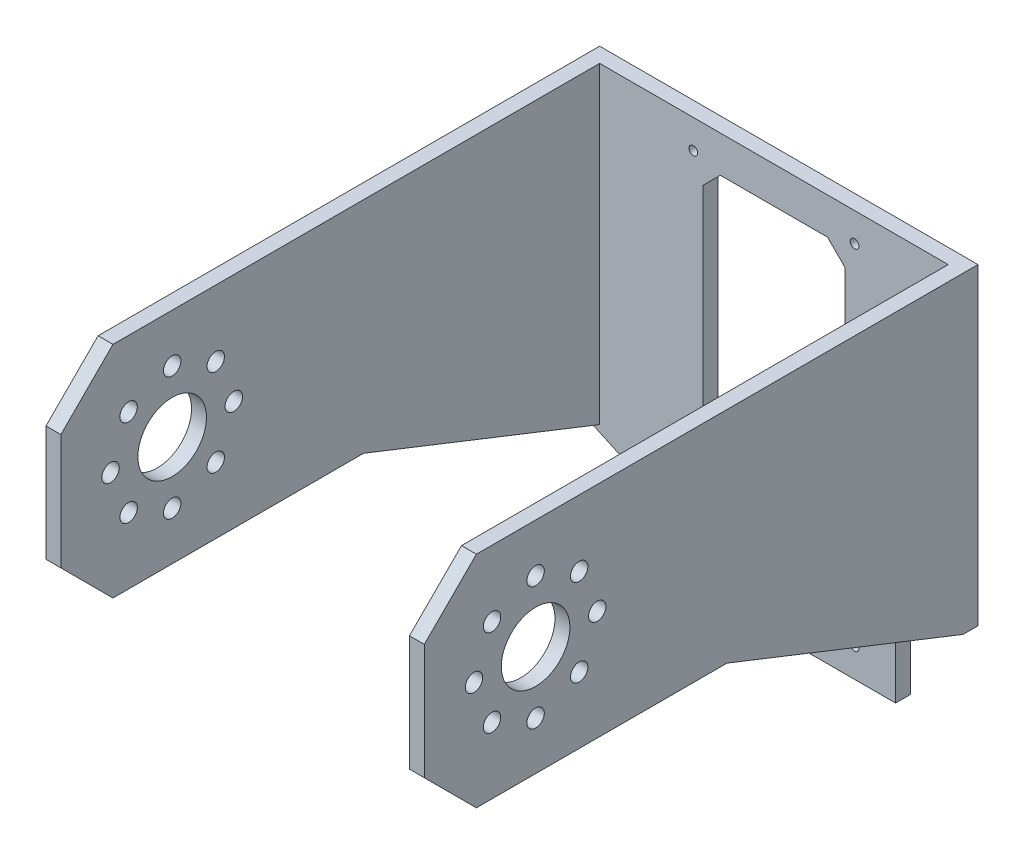
SolidWorks part; units mm, degrees
ref_plane "Front Plane" through (0, 0, 0) normal (0, 0, 1) x (1, 0, 0)
ref_plane "Top Plane" through (0, 0, 0) normal (0, 1, 0) x (1, 0, 0)
ref_plane "Right Plane" through (0, 0, 0) normal (1, 0, 0) x (0, 0, -1)
sketch "Sketch1" plane through (0, 0, -0.0877) normal (0, 1, 0) x (1, 0, 0)
  line L0 (0, 0) -> (-21.71, 0)
  line L1 (-21.71, 0) -> (-21.71, -63.54)
  line L2 (-21.71, -63.54) -> (-20, -63.54)
  line L3 (-20, -63.54) -> (-20, -1.71)
  line L4 (-20, -1.71) -> (0, -1.71)
  line L5 (0, -1.71) -> (0, 0)
  dimension "D1" = 1.71
  dimension "D2" = 1.71
  dimension "D3" = 20
  dimension "D4" = 63.54
extrude "Boss-Extrude1" add sketch "Sketch1" along normal mid plane 25.21
sketch "Sketch2" plane through (-21.71, 0, -0.0877) normal (-1, 0, 0) x (0, 0, 1)
  line L0 (57.565, 12.605) -> (63.54, 6.63)
  line L1 (0, 12.605) -> (63.54, 12.605) construction
  line L2 (63.54, 12.605) -> (63.54, -12.605) construction
  line L3 (63.54, 6.63) -> (63.54, -6.63) construction
  line L4 (63.54, -6.63) -> (57.565, -12.605)
  line L5 (0, -12.605) -> (63.54, -12.605) construction
  line L6 (57.565, -12.605) -> (57.565, 12.605) construction
  line L7 (0.0877, 0) -> (63.54, 0) construction
  line L8 (57.565, 12.605) -> (63.54, 12.605)
  line L9 (63.54, 12.605) -> (63.54, 6.63)
  line L10 (57.565, -12.605) -> (63.54, -12.605)
  line L11 (63.54, -12.605) -> (63.54, -6.63)
  point P11 (63.54, 0)
  dimension "D1" = 13.26
  dimension "D2" = 45
extrude "Cut-Extrude1" cut sketch "Sketch2" against normal blind 32.2
sketch "Sketch3" plane through (-21.71, 0, -0.0877) normal (-1, 0, 0) x (0, 0, 1)
  line L0 (50.77, 12.25) -> (50.77, 0) construction
  line L1 (55.77, -5) -> (45.77, -5) construction
  line L2 (55.77, -5) -> (55.77, 5) construction
  line L3 (55.77, 5) -> (45.77, 5) construction
  line L4 (45.77, -5) -> (45.77, 5) construction
  line L5 (55.77, -5) -> (45.77, 5) construction
  line L6 (55.77, 5) -> (45.77, -5) construction
  line L7 (50.77, 0) -> (63.54, 0) construction
  line L8 (63.54, 6.63) -> (63.54, -6.63) construction
  circle A0 centre (50.77, 0) radius 3.935
  circle A1 centre (45.77, 5) radius 1
  circle A2 centre (55.77, 5) radius 1
  circle A3 centre (55.77, -5) radius 1
  circle A4 centre (45.77, -5) radius 1
  circle A5 centre (50.77, 0) radius 7.0711 construction
  circle A6 centre (43.6989, 0) radius 1
  circle A7 centre (50.77, -7.0711) radius 1
  circle A8 centre (57.8411, 0) radius 1
  circle A9 centre (50.77, 7.0711) radius 1
  dimension "D1" = 7.87
  dimension "D3" = 2
  dimension "D2" = 45
  dimension "D4" = 10
  dimension "D5" = 12.77
extrude "Cut-Extrude2" cut sketch "Sketch3" against normal blind 32.2
mirror "Mirror1" about plane through (0, 12.605, 1.6223) normal (-1, 0, 0) of "Cut-Extrude1", "Boss-Extrude1", "Cut-Extrude2"
sketch "Sketch4" plane through (0, 0, 1.6223) normal (0, 0, 1) x (1, 0, 0)
  line L0 (0, 9.4948) -> (0, 0) construction
  line L1 (5, -5) -> (-5, -5) construction
  line L2 (5, -5) -> (5, 5) construction
  line L3 (5, 5) -> (-5, 5) construction
  line L4 (-5, -5) -> (-5, 5) construction
  line L5 (5, -5) -> (-5, 5) construction
  line L6 (5, 5) -> (-5, -5) construction
  line L7 (7.0711, 0) -> (0, 7.0711) construction
  line L8 (7.0711, 0) -> (0, -7.0711) construction
  line L9 (0, 7.0711) -> (-7.0711, 0) construction
  line L10 (0, -7.0711) -> (-7.0711, 0) construction
  line L11 (7.0711, 0) -> (-7.0711, 0) construction
  line L12 (0, 7.0711) -> (0, -7.0711) construction
  circle A0 centre (0, 0) radius 3.935
  circle A1 centre (-5, 5) radius 1
  circle A2 centre (5, 5) radius 1
  circle A3 centre (5, -5) radius 1
  circle A4 centre (-5, -5) radius 1
  circle A5 centre (-7.0711, 0) radius 1
  circle A6 centre (0, 7.0711) radius 1
  circle A7 centre (7.0711, 0) radius 1
  circle A8 centre (0, -7.0711) radius 1
  dimension "D1" = 7.87
  dimension "D3" = 2
  dimension "D6" = 10
  dimension "D2" = 45
  dimension "D4" = 10
  dimension "D5" = 45
extrude "Cut-Extrude3" [suppressed] cut sketch "Sketch4" against normal blind 32.2
chamfer "Chamfer1" [suppressed] distance 6 angle 45
chamfer "Chamfer2" [suppressed] distance 7 angle 45
sketch "Sketch5" plane through (0, -12.605, -0.0877) normal (0, -1, 0) x (1, 0, 0)
  line L0 (-21.71, 28.8) -> (-20, 28.8)
  line L1 (-21.71, 0) -> (-21.71, 57.565) construction
  line L2 (-20, 57.565) -> (-20, 1.71) construction
  line L3 (-20, 28.8) -> (-20, 1.71)
  line L4 (-20, 1.71) -> (20, 1.71)
  line L5 (20, 1.71) -> (20, 28.8)
  line L6 (20, 57.565) -> (20, 1.71) construction
  line L7 (20, 28.8) -> (21.71, 28.8)
  line L8 (21.71, 0) -> (21.71, 57.565) construction
  line L9 (21.71, 28.8) -> (21.71, 0)
  line L10 (21.71, 0) -> (-21.71, 0)
  line L11 (-21.71, 0) -> (-21.71, 28.8)
  line L12 (-20, 28.8) -> (20, 28.8) construction
  dimension "D1" = 28.8
extrude "Boss-Extrude2" add sketch "Sketch5" along normal blind 21.39
sketch "Sketch6" plane through (0, 0, -0.0877) normal (0, 0, -1) x (-1, 0, 0)
  line L0 (-21.71, 12.605) -> (-21.71, -33.995) construction
  line L1 (-21.71, -26.845) -> (-13.96, -26.845) construction
  line L2 (-21.71, -26.845) -> (-21.71, -33.995)
  line L3 (-21.71, -33.995) -> (-13.96, -33.995)
  line L4 (-13.96, -26.845) -> (-13.96, -33.995)
  line L5 (21.71, -33.995) -> (-21.71, -33.995) construction
  line L6 (-21.71, -26.845) -> (-21.71, -23.295)
  line L7 (-21.71, -23.295) -> (-13.96, -26.845)
  line L8 (0, -33.995) -> (0, 0) construction
  line L9 (21.71, -26.845) -> (13.96, -26.845) construction
  line L10 (21.71, -23.295) -> (13.96, -26.845)
  line L11 (21.71, -26.845) -> (21.71, -23.295)
  line L12 (13.96, -26.845) -> (13.96, -33.995)
  line L13 (21.71, -33.995) -> (13.96, -33.995)
  line L14 (21.71, -26.845) -> (21.71, -33.995)
  line L15 (-21.71, 12.605) -> (21.71, 12.605) construction
  line L16 (-8.15, 8.405) -> (8.15, 8.405)
  line L17 (-8.15, 8.405) -> (-8.15, -29.795)
  line L18 (-8.15, -29.795) -> (8.15, -29.795)
  line L19 (8.15, 8.405) -> (8.15, -29.795)
  line L20 (-8.15, 8.405) -> (8.15, -29.795) construction
  line L21 (-8.15, -29.795) -> (8.15, 8.405) construction
  line L23 (9.25, 9.305) -> (-9.25, 9.305) construction
  line L24 (9.25, 9.305) -> (9.25, -30.695) construction
  line L25 (9.25, -30.695) -> (-9.25, -30.695) construction
  line L26 (-9.25, 9.305) -> (-9.25, -30.695) construction
  line L27 (9.25, 9.305) -> (-9.25, -30.695) construction
  line L28 (9.25, -30.695) -> (-9.25, 9.305) construction
  circle A0 centre (-9.25, 9.305) radius 0.5
  circle A1 centre (9.25, 9.305) radius 0.5
  circle A2 centre (9.25, -30.695) radius 0.5
  circle A3 centre (-9.25, -30.695) radius 0.5
  point P17 (0, -10.695)
  point P24 (0, 12.605)
  point P25 (0, -10.695)
  dimension "D7" = 18.5
  dimension "D1" = 7.15
  dimension "D2" = 10.7
  dimension "D3" = 16.3
  dimension "D4" = 38.2
  dimension "D5" = 4.2
  dimension "D6" = 7.75
  dimension "D8" = 40
extrude "Cut-Extrude4" cut sketch "Sketch6" against normal blind 45
sketch "Sketch7" plane through (21.71, 0, 0) normal (1, 0, 0) x (0, 0, -1)
  line L0 (-28.7123, -12.605) -> (-1.6223, -23.295)
  line L1 (-28.7123, -23.295) -> (0.0877, -23.295) construction
  line L2 (-1.6223, -23.295) -> (-1.6223, -35.5938)
  line L3 (-1.6223, -35.5938) -> (-28.7123, -35.5938)
  line L4 (-28.7123, -35.5938) -> (-28.7123, -12.605)
extrude "Cut-Extrude5" cut sketch "Sketch7" against normal blind 68
chamfer "Chamfer3" distance 2 angle 45 4 edges at (8.15, 8.405, 0.7673) (-8.15, 8.405, 0.7673) (8.15, -29.795, 0.7673) (-8.15, -29.795, 0.7673)
